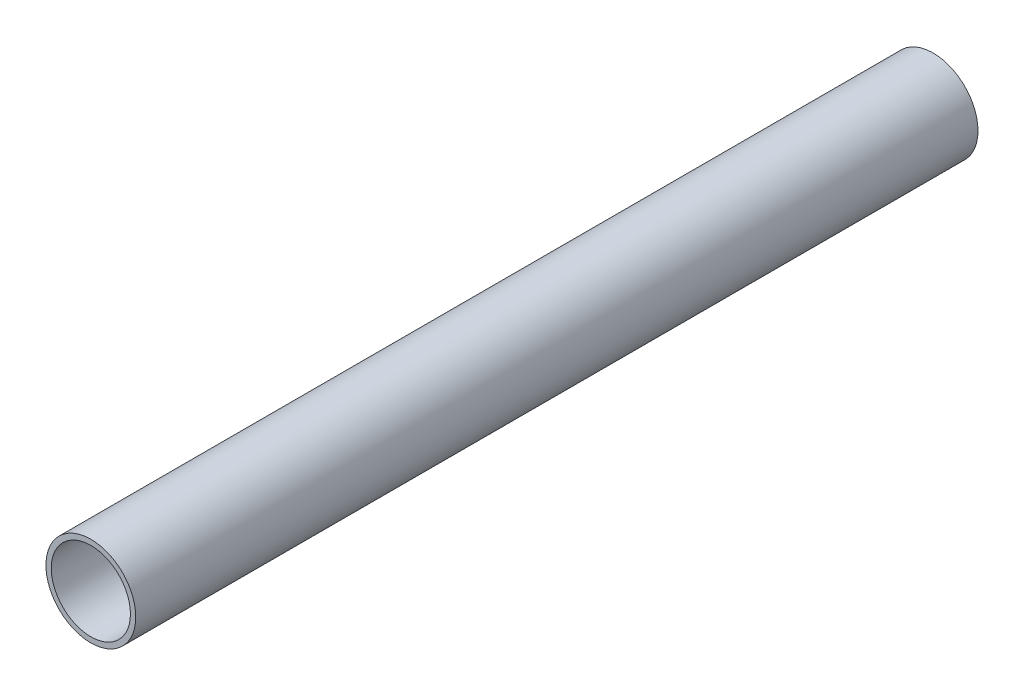
SolidWorks part; units mm, degrees
material "PE Высокой плотности"
ref_plane "Front" through (0, 0, 0) normal (0, 0, 1) x (1, 0, 0)
ref_plane "Top" through (0, 0, 0) normal (0, 1, 0) x (1, 0, 0)
ref_plane "Side" through (0, 0, 0) normal (1, 0, 0) x (0, 0, -1)
sketch "PipeSketch" plane through (0, 0, 0) normal (0, 0, 1) x (1, 0, 0)
  circle A0 centre (0, 0) radius 16
  circle A1 centre (0, 0) radius 14.1
  dimension "OuterDiameter" = 32
  dimension "InnerDiameter" = 28.2
extrude "Extrusion" add sketch "PipeSketch" along normal blind 300
sketch "FilterSketch" plane through (0, 0, 0) normal (0, 0, 1) x (1, 0, 0)
  circle A0 centre (0, 0) radius 16 construction
  dimension "NominalDiameter" = 32
